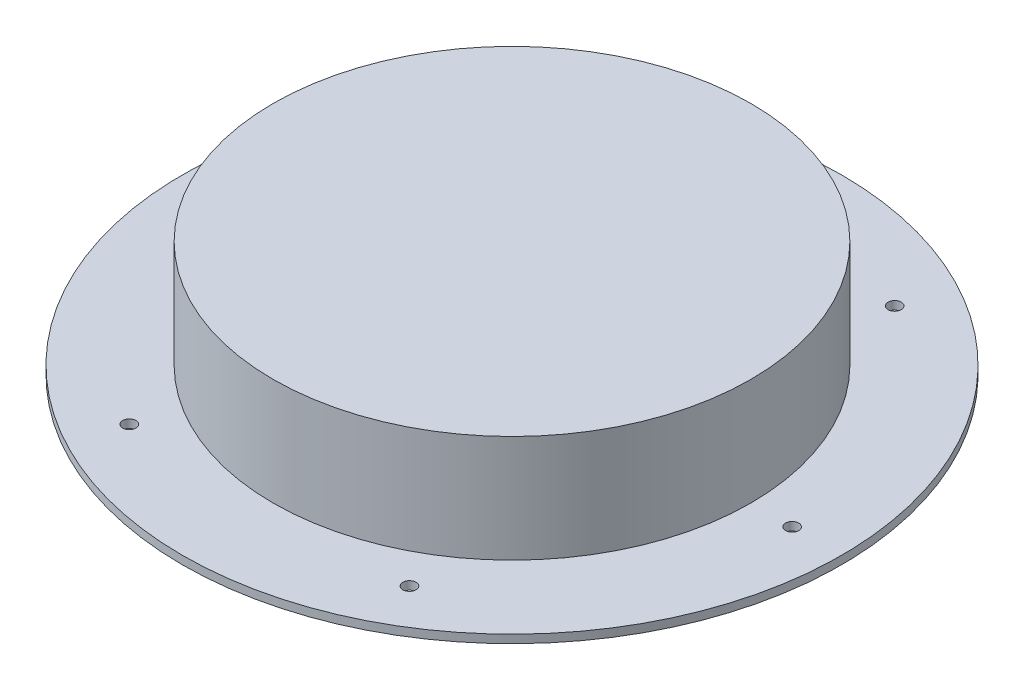
SolidWorks part; units mm, degrees
ref_plane "Front Plane" through (0, 0, 0) normal (0, 0, 1) x (1, 0, 0)
ref_plane "Top Plane" through (0, 0, 0) normal (0, 1, 0) x (1, 0, 0)
ref_plane "Right Plane" through (0, 0, 0) normal (1, 0, 0) x (0, 0, -1)
sketch "Sketch1" plane through (0, 0, 0) normal (0, 1, 0) x (1, 0, 0)
  circle A0 centre (0, 0) radius 100
  circle A1 centre (0, 0) radius 70
  dimension "D1" = 200
  dimension "D2" = 140
extrude "Boss-Extrude1" add sketch "Sketch1" along normal blind 2.5
sketch "Sketch2" plane through (0, 2.5, 0) normal (0, 1, 0) x (1, 0, 0)
  circle A0 centre (0, 0) radius 72.5
  circle A1 centre (0, 0) radius 70 construction
  circle A2 centre (0, 0) radius 70
  dimension "D1" = 2.5
extrude "Boss-Extrude2" add sketch "Sketch2" along normal blind 30
sketch "Sketch3" plane through (0, 32.5, 0) normal (0, 1, 0) x (1, 0, 0)
  circle A0 centre (0, 0) radius 72.5
  circle A1 centre (0, 0) radius 72.5 construction
extrude "Boss-Extrude3" add sketch "Sketch3" along normal blind 2.5
sketch "Sketch5" plane through (0, 0, 0) normal (0, -1, 0) x (1, 0, 0)
  circle A0 centre (0, 0) radius 70 construction
  circle A1 centre (0, 0) radius 70
  arc A2 (69.2857, 9.9745) -> (69.2857, -9.9745) centre (70, 0) ccw
  arc A3 (43.281, -55.016) -> (26.0047, -64.9904) centre (35, -60.6218) ccw
  arc A4 (-26.0047, -64.9904) -> (-43.281, -55.016) centre (-35, -60.6218) ccw
  arc A5 (-69.2857, -9.9745) -> (-69.2857, 9.9745) centre (-70, 0) ccw
  arc A6 (-43.281, 55.016) -> (-26.0047, 64.9904) centre (-35, 60.6218) ccw
  arc A7 (26.0047, 64.9904) -> (43.281, 55.016) centre (35, 60.6218) ccw
  point P24 (0, 0)
  circle M2 centre (0, 0) radius 70
  dimension "D1" = 20
  dimension "D2" = 6
extrude "Boss-Extrude4" add sketch "Sketch5" against normal blind 5 contours A2 M2 | A7 M2 | A6 M2 | A5 M2 | A4 M2 | A3 M2
sketch "Sketch4" plane through (0, 2.5, 0) normal (0, 1, 0) x (1, 0, 0)
  line L0 (0, 0) -> (85, 0) construction
  circle A0 centre (85, 0) radius 2
  circle A1 centre (65, 0) radius 2
  circle A2 centre (32.5, -56.2917) radius 2
  circle A3 centre (42.5, -73.6122) radius 2
  circle A4 centre (-32.5, -56.2917) radius 2
  circle A5 centre (-42.5, -73.6122) radius 2
  circle A6 centre (-65, 0) radius 2
  circle A7 centre (-85, 0) radius 2
  circle A8 centre (-32.5, 56.2917) radius 2
  circle A9 centre (-42.5, 73.6122) radius 2
  circle A10 centre (32.5, 56.2917) radius 2
  circle A11 centre (42.5, 73.6122) radius 2
  point P28 (0, 0)
  dimension "D1" = 4
  dimension "D2" = 4
  dimension "D3" = 65
  dimension "D4" = 85
  dimension "D5" = 6
extrude "Cut-Extrude1" cut sketch "Sketch4" along normal blind 5 and the other way through all
